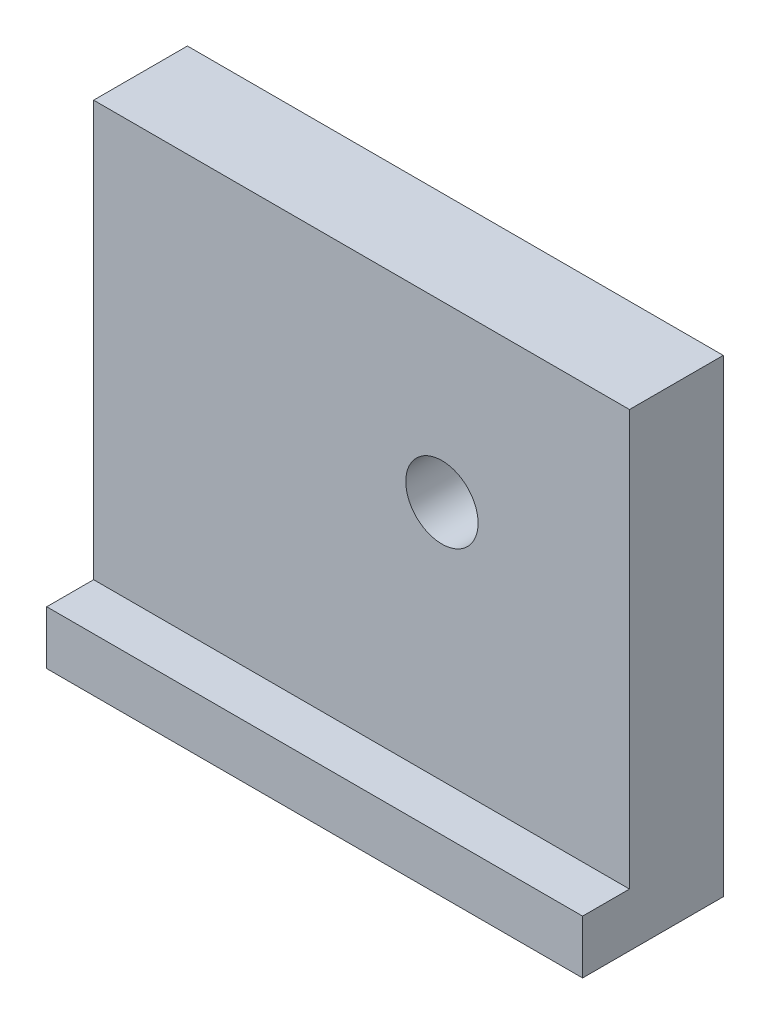
SolidWorks part; units mm, degrees
ref_plane "前视基准面" through (0, 0, 0) normal (0, 0, 1) x (1, 0, 0)
ref_plane "上视基准面" through (0, 0, 0) normal (0, 1, 0) x (1, 0, 0)
ref_plane "右视基准面" through (0, 0, 0) normal (1, 0, 0) x (0, 0, -1)
sketch "草图1" plane through (0, 0, 0) normal (0, 0, 1) x (1, 0, 0)
  line L9 (-20, 35) -> (20, 35)
  line L10 (-20, 35) -> (-20, 0)
  line L11 (-20, 0) -> (20, 0)
  line L12 (20, 35) -> (20, 0)
  line L13 (-20, 35) -> (20, 0) construction
  line L14 (-20, 0) -> (20, 35) construction
  circle A1 centre (15, 10) radius 2.5 construction
  circle A2 centre (6, 22) radius 2.7
  point P0 (0, 0)
  point P1 (0, 17.5)
  dimension "D3" = 5
  dimension "D8" = 5.4
  dimension "D1" = 35
  dimension "D2" = 40
  dimension "D4" = 10
  dimension "D5" = 15
  dimension "D6" = 12
  dimension "D7" = 9
extrude "凸台-拉伸1" add sketch "草图1" along normal mid plane 7
sketch "草图2" plane through (0, 0, 0) normal (0, 0, 1) x (1, 0, 0)
  line L0 (20, 0) -> (20, 35) construction
  line L1 (-20, 0) -> (20, 0)
  line L2 (-20, 0) -> (-20, 4)
  line L3 (-20, 4) -> (20, 4)
  line L4 (20, 0) -> (20, 4)
  dimension "D1" = 4
extrude "凸台-拉伸2" add sketch "草图2" along normal blind 7
